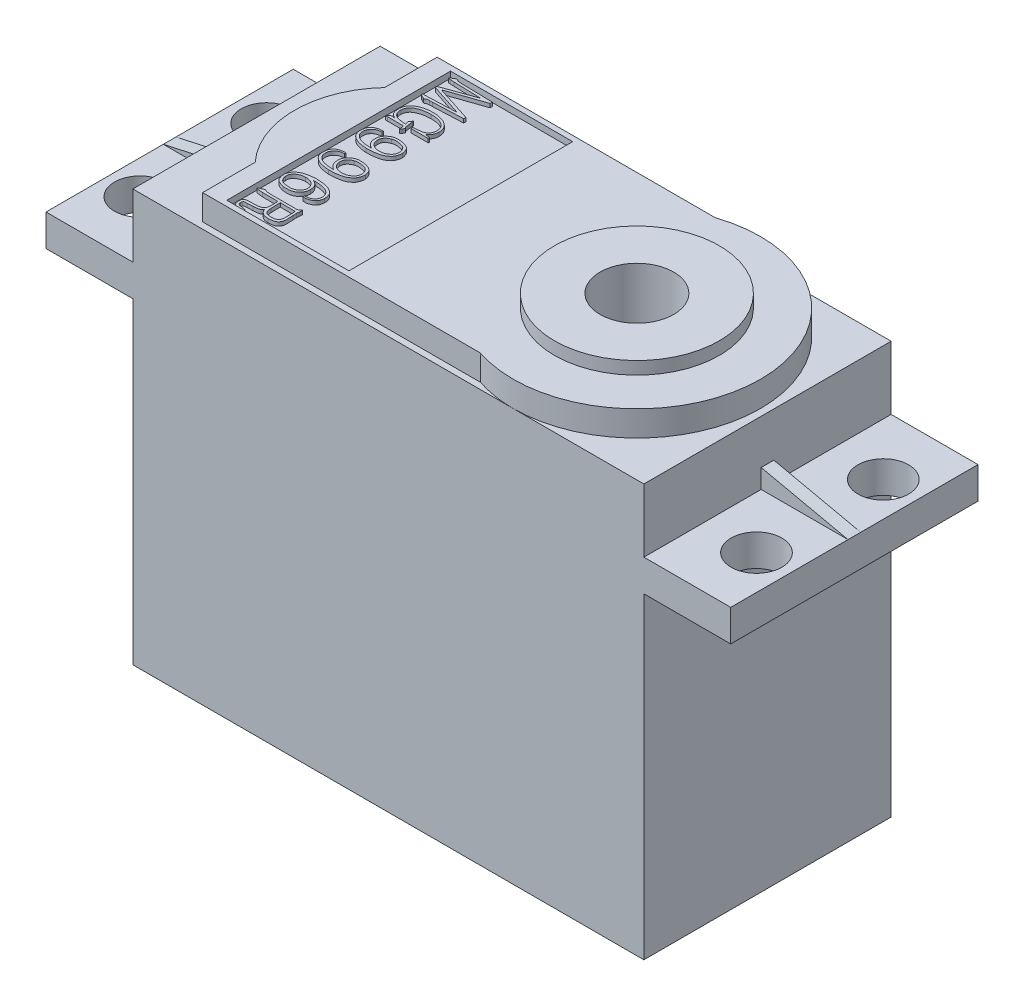
SolidWorks part; units mm, degrees
material "CA"
ref_plane "前视基准面" through (0, 0, 0) normal (0, 0, 1) x (1, 0, 0)
ref_plane "上视基准面" through (0, 0, 0) normal (0, 1, 0) x (1, 0, 0)
ref_plane "右视基准面" through (0, 0, 0) normal (1, 0, 0) x (0, 0, -1)
sketch "草图1" plane through (0, 0, 0) normal (0, 1, 0) x (1, 0, 0)
  line L1 (-20.15, 9.75) -> (20.15, 9.75)
  line L2 (-20.15, 9.75) -> (-20.15, -9.75)
  line L3 (-20.15, -9.75) -> (20.15, -9.75)
  line L4 (20.15, 9.75) -> (20.15, -9.75)
  line L5 (-20.15, 9.75) -> (20.15, -9.75) construction
  line L6 (-20.15, -9.75) -> (20.15, 9.75) construction
  point P0 (0, 0)
  dimension "D1" = 40.3
  dimension "D2" = 19.5
extrude "凸台-拉伸1" add sketch "草图1" along normal blind 27
sketch "草图2" plane through (0, 27, 0) normal (0, 1, 0) x (1, 0, 0)
  line L1 (-27, 9.75) -> (27, 9.75)
  line L2 (-27, 9.75) -> (-27, -9.75)
  line L3 (-27, -9.75) -> (27, -9.75)
  line L4 (27, 9.75) -> (27, -9.75)
  line L5 (-27, 9.75) -> (27, -9.75) construction
  line L6 (-27, -9.75) -> (27, 9.75) construction
  point P0 (0, 0)
  dimension "D1" = 54
  dimension "D2" = 19.5
extrude "凸台-拉伸2" add sketch "草图2" along normal blind 2.5
sketch "草图3" plane through (0, 29.5, 0) normal (0, 1, 0) x (1, 0, 0)
  line L0 (-27, -9.75) -> (27, -9.75) construction
  line L1 (-20.15, 9.75) -> (20.15, 9.75)
  line L2 (-20.15, 9.75) -> (-20.15, -9.75)
  line L3 (-20.15, -9.75) -> (20.15, -9.75)
  line L4 (20.15, 9.75) -> (20.15, -9.75)
  line L5 (-20.15, 9.75) -> (20.15, -9.75) construction
  line L6 (-20.15, -9.75) -> (20.15, 9.75) construction
  line L7 (-27, 9.75) -> (-27, -9.75) construction
  point P0 (0, 0)
  dimension "D1" = 6.85
extrude "凸台-拉伸3" add sketch "草图3" along normal blind 5
sketch "草图4" plane through (0, 34.5, 0) normal (0, 1, 0) x (1, 0, 0)
  line L0 (27, -9.75) -> (27, 9.75) construction
  line L1 (20.15, 9.75) -> (-20.15, 9.75) construction
  line L2 (-28.674, 0) -> (31.5591, 0) construction
  line L3 (-15.15, -9.25) -> (-15.15, -5.099)
  line L4 (-15.15, 9.25) -> (6.7678, 9.25)
  line L5 (-20.15, 9.75) -> (-20.15, -9.75) construction
  line L6 (-15.15, -9.25) -> (6.7678, -9.25)
  line L7 (-20.15, -9.75) -> (20.15, -9.75) construction
  line L8 (-20.15, 9.75) -> (-20.15, -9.75) construction
  line L9 (-15.15, 5.099) -> (-15.15, 9.25)
  arc A0 (6.7678, -9.25) -> (6.7678, 9.25) centre (9.85, 0) ccw
  arc A1 (-15.15, 5.099) -> (-15.15, -5.099) centre (-9.65, 0) ccw
  point P15 (-15.15, 0)
  dimension "D4" = 15
  dimension "D1" = 17.15
  dimension "D2" = 5
  dimension "D3" = 0.5
  dimension "D5" = 10.5
extrude "凸台-拉伸4" add sketch "草图4" along normal blind 2
ref_plane "基准面1" through (0, 0, 0) normal (0, 0, 1) x (1, 0, 0)
sketch "草图5" plane through (0, 0, 0) normal (0, 0, 1) x (1, 0, 0)
  line L2 (20.15, 31) -> (27, 29.5)
  line L3 (20.15, 34.5) -> (20.15, 29.5) construction
  line L4 (20.15, 29.5) -> (27, 29.5) construction
  line L5 (27, 29.5) -> (27, 27) construction
  dimension "D2" = 1.5
rib "筋1" sketch "草图5" sketch "草图5" thickness 1 extrusion direction parallel to sketch draft on no parameters "D1"=1
sketch "草图6" plane through (0, 0, 0) normal (0, 0, 1) x (1, 0, 0)
  line L0 (-20.15, 31) -> (-27, 29.5)
  line L1 (-20.15, 34.5) -> (-20.15, 29.5) construction
  dimension "D1" = 1.5
rib "筋2" sketch "草图6" sketch "草图6" thickness 1 extrusion direction parallel to sketch draft on no parameters "D1"=1
sketch "草图7" plane through (0, 36.5, 0) normal (0, 1, 0) x (1, 0, 0)
  circle A0 centre (9.85, 0) radius 6.5
  dimension "D1" = 13
extrude "凸台-拉伸5" add sketch "草图7" along normal blind 1
sketch "草图8" plane through (0, 37.5, 0) normal (0, 1, 0) x (1, 0, 0)
  circle A0 centre (9.85, 0) radius 2.9
  dimension "D1" = 5.8
extrude "切除-拉伸1" cut sketch "草图8" against normal blind 5
sketch "草图9" plane through (0, 29.5, 0) normal (0, 1, 0) x (1, 0, 0)
  line L0 (-32.7219, 0) -> (36.2848, 0) construction
  line L2 (-27, 9.75) -> (-27, 0.5) construction
  circle A0 centre (-24.35, 5) radius 2
  circle A1 centre (24.28, 5) radius 2
  circle A4 centre (24.28, -5) radius 2
  circle A5 centre (-24.35, -5) radius 2
  dimension "D3" = 4
  dimension "D4" = 4
  dimension "D1" = 5
  dimension "D2" = 5
  dimension "D5" = 48.63
  dimension "D6" = 2.65
extrude "切除-拉伸2" cut sketch "草图9" against normal blind 5
chamfer "倒角1" distance 2 angle 45 4 edges at (-20.15, 0, 0) (0, 0, -9.75) (20.15, 0, 0) (0, 0, 9.75)
sketch "草图10" plane through (0, 36.5, 0) normal (0, 1, 0) x (1, 0, 0)
  line L0 (-17.875, 0) -> (17.875, 0) construction
  line L1 (-13.673, 8.8233) -> (-4.0362, 8.8233)
  line L2 (-13.673, 8.8233) -> (-13.673, -8.8233)
  line L3 (-13.673, -8.8233) -> (-4.0362, -8.8233)
  line L4 (-4.0362, 8.8233) -> (-4.0362, -8.8233)
  line L5 (-13.673, 8.8233) -> (-4.0362, -8.8233) construction
  line L6 (-13.673, -8.8233) -> (-4.0362, 8.8233) construction
  line L7 (-27, 9.75) -> (-27, 0.5) construction
  point P0 (-8.8546, 0)
  dimension "D1" = 13.327
  dimension "D2" = 9.6368
  dimension "D3" = 17.6466
extrude "切除-拉伸3" cut sketch "草图10" against normal blind 0.5
sketch "草图11" plane through (0, 36, 0) normal (0, 1, 0) x (1, 0, 0)
  text T0 "MG996R" font "汉仪长仿宋体" height 3.5
extrude "凸台-拉伸6" add sketch "草图11" along normal blind 0.3
